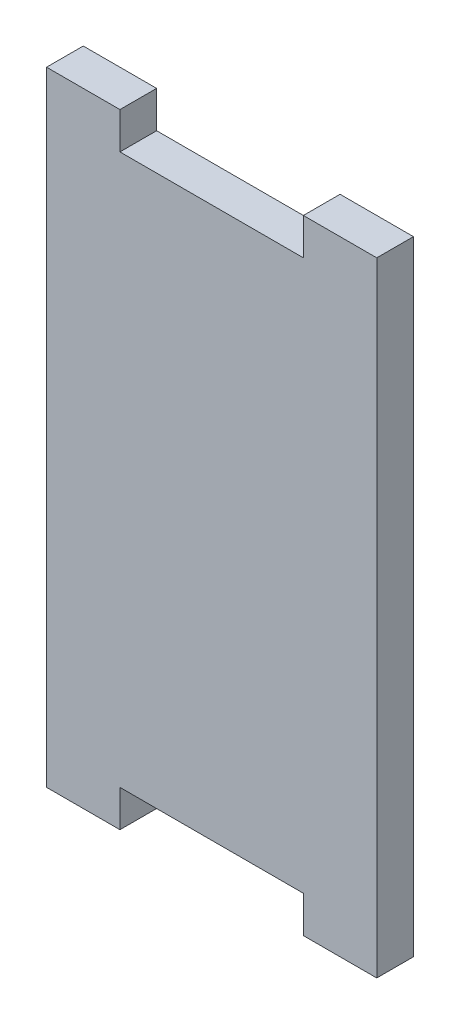
SolidWorks part; units mm, degrees
ref_plane "Plan de face" through (0, 0, 0) normal (0, 0, 1) x (1, 0, 0)
ref_plane "Plan de dessus" through (0, 0, 0) normal (0, 1, 0) x (1, 0, 0)
ref_plane "Plan de droite" through (0, 0, 0) normal (1, 0, 0) x (0, 0, -1)
sketch "Esquisse1" plane through (0, 0, 0) normal (0, 0, 1) x (1, 0, 0)
  line L1 (0, 0) -> (45, 0)
  line L2 (0, 0) -> (0, 75)
  line L3 (0, 75) -> (45, 75)
  line L4 (45, 0) -> (45, 75)
  dimension "D1" = 75
  dimension "D2" = 45
extrude "Boss.-Extru.1" add sketch "Esquisse1" along normal blind 5
sketch "Esquisse2" plane through (0, 0, 5) normal (0, 0, 1) x (1, 0, 0)
  line L1 (0, 75) -> (10, 75)
  line L2 (0, 75) -> (0, 80)
  line L3 (0, 80) -> (10, 80)
  line L4 (10, 75) -> (10, 80)
  line L5 (45, 75) -> (35, 75)
  line L6 (45, 75) -> (45, 80)
  line L7 (45, 80) -> (35, 80)
  line L8 (35, 75) -> (35, 80)
  line L9 (0, 0) -> (10, 0)
  line L10 (0, 0) -> (0, -5)
  line L11 (0, -5) -> (10, -5)
  line L12 (10, 0) -> (10, -5)
  line L13 (45, 0) -> (35, 0)
  line L14 (45, 0) -> (45, -5)
  line L15 (45, -5) -> (35, -5)
  line L16 (35, 0) -> (35, -5)
  dimension "D1" = 10
  dimension "D2" = 5
extrude "Boss.-Extru.2" add sketch "Esquisse2" against normal blind 5
